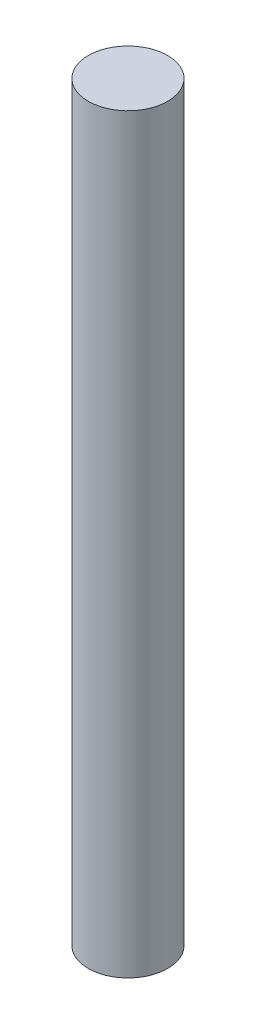
SolidWorks part; units mm, degrees
material "Alloy Steel"
ref_plane "Front Plane" through (0, 0, 0) normal (0, 0, 1) x (1, 0, 0)
ref_plane "Top Plane" through (0, 0, 0) normal (0, 1, 0) x (1, 0, 0)
ref_plane "Right Plane" through (0, 0, 0) normal (1, 0, 0) x (0, 0, -1)
sketch "Sketch1" plane through (0, 0, 0) normal (0, 1, 0) x (1, 0, 0)
  circle A0 centre (0, 0) radius 1.585
  dimension "D1" = 3.17
extrude "Boss-Extrude1" add sketch "Sketch1" along normal blind 30
